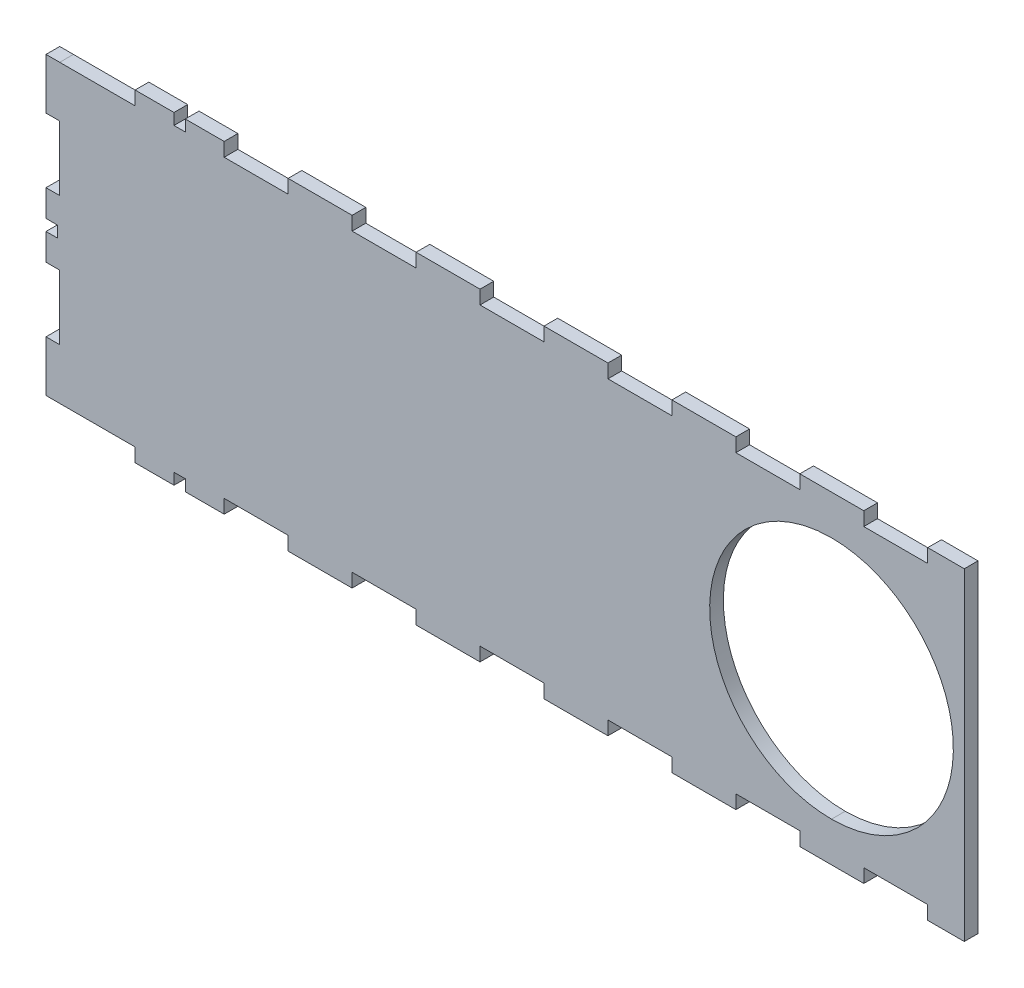
SolidWorks part; units mm, degrees
ref_plane "Front Plane" through (0, 0, 0) normal (0, 0, 1) x (1, 0, 0)
ref_plane "Top Plane" through (0, 0, 0) normal (0, 1, 0) x (1, 0, 0)
ref_plane "Right Plane" through (0, 0, 0) normal (1, 0, 0) x (0, 0, -1)
sketch "Model" plane through (0, 0, 0) normal (0, 0, 1) x (1, 0, 0)
  line L0 (760.0508, -1228.0025) -> (747.2757, -1228.0025)
  line L1 (747.2757, -1228.0025) -> (747.2757, -1232.5025)
  line L2 (747.2757, -1232.5025) -> (722.5258, -1232.5025)
  line L3 (923.5257, -1228.0025) -> (923.5257, -1232.5025)
  line L4 (923.5257, -1232.5025) -> (902.5258, -1232.5025)
  line L5 (902.5258, -1232.5025) -> (902.5258, -1228.0025)
  line L6 (902.5258, -1228.0025) -> (881.5259, -1228.0025)
  line L7 (881.5259, -1228.0025) -> (881.5259, -1232.5025)
  line L8 (881.5259, -1232.5025) -> (860.5256, -1232.5025)
  line L9 (860.5256, -1232.5025) -> (860.5256, -1228.0025)
  line L10 (860.5256, -1228.0025) -> (839.5257, -1228.0025)
  line L11 (839.5257, -1228.0025) -> (839.5257, -1232.5025)
  line L12 (839.5257, -1232.5025) -> (818.5258, -1232.5025)
  line L13 (818.5258, -1232.5025) -> (818.5258, -1228.0025)
  line L14 (818.5258, -1228.0025) -> (797.5255, -1228.0025)
  line L15 (797.5255, -1228.0025) -> (797.5255, -1232.5025)
  line L16 (797.5255, -1232.5025) -> (776.5256, -1232.5025)
  line L17 (776.5256, -1232.5025) -> (776.5256, -1228.0025)
  line L18 (776.5256, -1228.0025) -> (763.7508, -1228.0025)
  line L19 (760.0508, -1228.0025) -> (760.0508, -1231.7025)
  line L20 (760.0508, -1231.7025) -> (763.7508, -1231.7025)
  line L21 (763.7508, -1231.7025) -> (763.7508, -1228.0025)
  line L22 (923.5255, -1329.5023) -> (902.5254, -1329.5023)
  line L23 (902.5254, -1329.5023) -> (902.5254, -1334.0022)
  line L24 (902.5254, -1334.0022) -> (881.5255, -1334.0022)
  line L25 (881.5255, -1334.0022) -> (881.5255, -1329.5023)
  line L26 (881.5255, -1329.5023) -> (860.5256, -1329.5023)
  line L27 (860.5256, -1329.5023) -> (860.5256, -1334.0022)
  line L28 (860.5256, -1334.0022) -> (839.5257, -1334.0022)
  line L29 (839.5257, -1334.0022) -> (839.5257, -1329.5023)
  line L30 (839.5257, -1329.5023) -> (818.5258, -1329.5023)
  line L31 (818.5258, -1329.5023) -> (818.5258, -1334.0022)
  line L32 (818.5258, -1334.0022) -> (797.5255, -1334.0022)
  line L33 (797.5255, -1334.0022) -> (797.5255, -1329.5023)
  line L34 (797.5255, -1329.5023) -> (776.5256, -1329.5023)
  line L35 (776.5256, -1329.5023) -> (776.5256, -1334.0022)
  line L36 (776.5256, -1334.0022) -> (763.7508, -1334.0022)
  line L37 (763.7508, -1334.0022) -> (763.7508, -1330.3022)
  line L38 (763.7508, -1330.3022) -> (760.0508, -1330.3022)
  line L39 (760.0508, -1330.3022) -> (760.0508, -1334.0022)
  line L40 (760.0508, -1334.0022) -> (747.2757, -1334.0022)
  line L41 (747.2757, -1334.0022) -> (747.2757, -1329.5023)
  line L42 (747.2757, -1329.5023) -> (718.0258, -1329.5023)
  line L43 (718.0258, -1329.5023) -> (718.0258, -1312.8025)
  line L44 (718.0258, -1312.8025) -> (722.5258, -1312.8025)
  line L45 (722.5258, -1312.8025) -> (722.5258, -1291.6025)
  line L46 (722.5258, -1291.6025) -> (718.0258, -1291.6025)
  line L47 (718.0258, -1291.6025) -> (718.0258, -1282.8523)
  line L48 (718.0258, -1282.8523) -> (721.7258, -1282.8523)
  line L49 (721.7258, -1282.8523) -> (721.7258, -1279.1526)
  line L50 (721.7258, -1279.1526) -> (718.0258, -1279.1526)
  line L51 (718.0258, -1279.1526) -> (718.0258, -1270.4023)
  line L52 (718.0258, -1270.4023) -> (722.5258, -1270.4023)
  line L53 (722.5258, -1270.4023) -> (722.5258, -1249.2026)
  line L54 (722.5258, -1249.2026) -> (718.0258, -1249.2026)
  line L55 (718.0258, -1249.2026) -> (718.0258, -1232.5025)
  line L56 (718.0258, -1232.5025) -> (722.5258, -1232.5025)
  line L57 (944.5256, -1228.0025) -> (923.5257, -1228.0025)
  line L58 (944.5256, -1232.5025) -> (944.5256, -1228.0025)
  line L59 (965.5256, -1232.5025) -> (944.5256, -1232.5025)
  line L60 (965.5256, -1232.5025) -> (965.5256, -1228.0101)
  line L61 (986.5255, -1228.0101) -> (965.5256, -1228.0101)
  line L62 (986.5255, -1232.5101) -> (986.5255, -1228.0101)
  line L63 (1007.5254, -1232.5101) -> (986.5255, -1232.5101)
  line L64 (1007.5254, -1232.5101) -> (1007.5254, -1227.995)
  line L65 (1007.5254, -1227.995) -> (1019.5257, -1228.0101)
  line L66 (1019.5257, -1228.0101) -> (1019.5257, -1334.0022)
  line L67 (923.5255, -1334.0022) -> (923.5255, -1329.5023)
  line L68 (944.5254, -1334.0022) -> (923.5255, -1334.0022)
  line L69 (944.5254, -1329.5023) -> (944.5254, -1334.0022)
  line L70 (965.5254, -1329.5023) -> (944.5254, -1329.5023)
  line L71 (965.5254, -1334.0022) -> (965.5254, -1329.5023)
  line L72 (986.5253, -1334.0022) -> (965.5254, -1334.0022)
  line L73 (986.5253, -1329.5023) -> (986.5253, -1334.0022)
  line L74 (1007.5256, -1329.5023) -> (986.5253, -1329.5023)
  line L75 (1007.5256, -1329.5023) -> (1007.5256, -1334.0022)
  line L76 (1007.5256, -1334.0022) -> (1019.5257, -1334.0022)
  spline S0 degree 3 poles (975.9285, -1321.0024) (953.8371, -1321.0024) (935.9284, -1303.0938) (935.9284, -1281.0024) (935.9284, -1258.9111) (953.8371, -1241.0024) (975.9285, -1241.0024) knots 2 2 2 2 3 3 3 4 4 4 4
  spline S1 degree 3 poles (975.9285, -1241.0024) (998.02, -1241.0024) (1015.9287, -1258.9111) (1015.9287, -1281.0024) (1015.9287, -1303.0938) (998.02, -1321.0024) (975.9285, -1321.0024) knots 0 0 0 0 1 1 1 2 2 2 2
extrude "Boss-Extrude1" add sketch "Model" along normal blind 4.5
